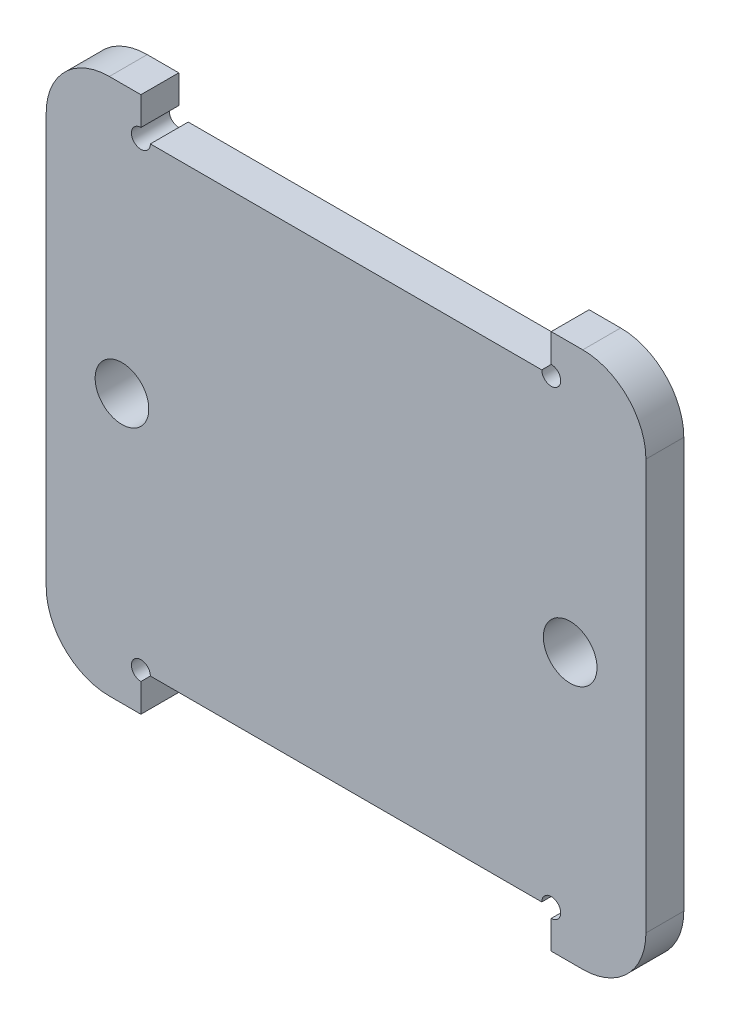
SolidWorks part; units mm, degrees
material "Plain Carbon Steel"
ref_plane "Front Plane" through (0, 0, 0) normal (0, 0, 1) x (1, 0, 0)
ref_plane "Top Plane" through (0, 0, 0) normal (0, 1, 0) x (1, 0, 0)
ref_plane "Right Plane" through (0, 0, 0) normal (1, 0, 0) x (0, 0, -1)
sketch "Sketch1" plane through (0, 0, 0) normal (0, 0, 1) x (1, 0, 0)
  line L0 (-351.5, 26) -> (-351.5, 99) construction
  line L1 (-334.5, 26) -> (-368.5, 26) construction
  line L2 (-368.5, 99) -> (-334.5, 99) construction
  line L3 (-384, 99) -> (-319, 99)
  line L4 (-319, 99) -> (-319, 105)
  line L6 (-319, 105) -> (-314, 105)
  line L7 (-304, 95) -> (-304, 30)
  line L8 (-314, 20) -> (-319, 20)
  line L9 (-319, 20) -> (-319, 26)
  line L10 (-329.5, 26) -> (-334.5, 26) construction
  line L12 (-319, 26) -> (-384, 26)
  line L13 (-304, 62.5) -> (-399, 62.5) construction
  line L14 (-384, 20) -> (-384, 26)
  line L15 (-389, 20) -> (-384, 20)
  line L16 (-399, 95) -> (-399, 30)
  line L17 (-384, 105) -> (-389, 105)
  line L18 (-384, 99) -> (-384, 105)
  line L19 (-319, 26) -> (-319, 20) construction
  line L20 (-329.5, 20) -> (-319, 20) construction
  line L21 (-319, 105) -> (-319, 99) construction
  arc A0 (-314, 105) -> (-304, 95) centre (-314, 95) cw
  arc A1 (-304, 30) -> (-314, 20) centre (-314, 30) cw
  circle A2 centre (-316, 62.5) radius 4.25
  circle A3 centre (-387, 62.5) radius 4.25
  arc A4 (-399, 30) -> (-389, 20) centre (-389, 30) ccw
  arc A5 (-389, 105) -> (-399, 95) centre (-389, 95) ccw
  point P29 (-351.5, 62.5)
  dimension "D1" = 10
  dimension "D2" = 8.5
  dimension "D3" = 5
  dimension "D4" = 12
extrude "Boss-Extrude1" add sketch "Sketch1" along normal blind 6
sketch "Sketch2" plane through (0, 0, 6) normal (0, 0, 1) x (1, 0, 0)
  line L0 (-351.5, 26) -> (-351.5, 99) construction
  line L1 (-384, 26) -> (-319, 26) construction
  line L2 (-319, 99) -> (-384, 99) construction
  line L3 (-304, 62.5) -> (-399, 62.5) construction
  line L4 (-304, 30) -> (-304, 95) construction
  line L5 (-399, 95) -> (-399, 30) construction
  circle A0 centre (-384, 26) radius 1.5
  circle A1 centre (-319, 26) radius 1.5
  circle A2 centre (-384, 99) radius 1.5
  circle A3 centre (-319, 99) radius 1.5
  dimension "D1" = 3
extrude "Cut-Extrude1" cut sketch "Sketch2" against normal through all
